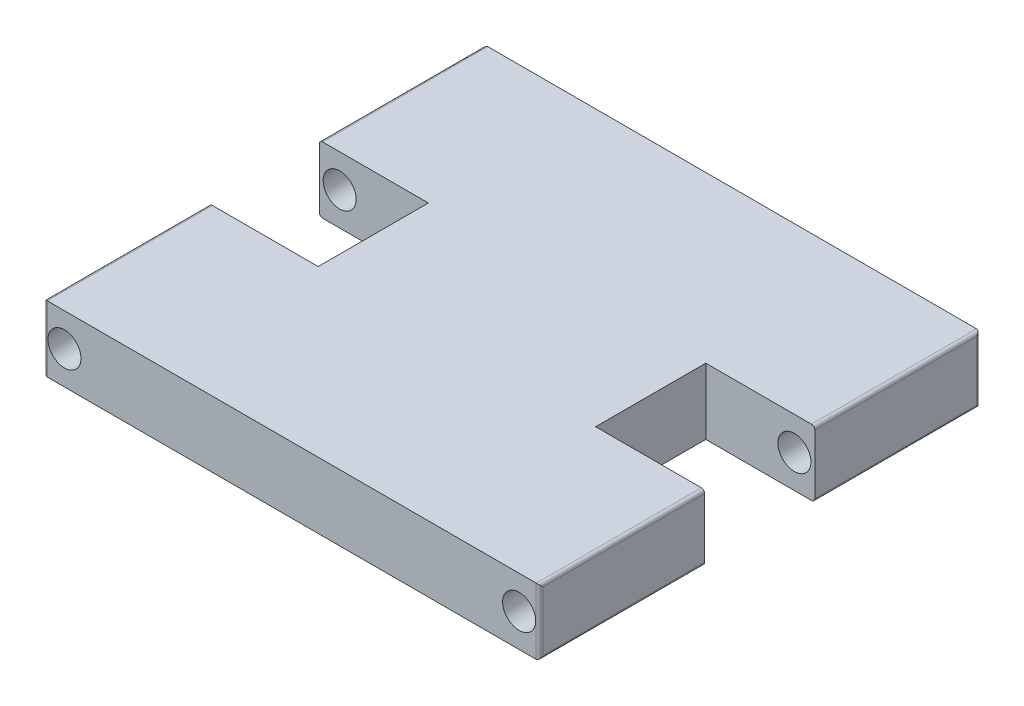
SolidWorks part; units mm, degrees
ref_plane "Piano frontale" through (0, 0, 0) normal (0, 0, 1) x (1, 0, 0)
ref_plane "Piano superiore" through (0, 0, 0) normal (0, 1, 0) x (1, 0, 0)
ref_plane "Piano destro" through (0, 0, 0) normal (1, 0, 0) x (0, 0, -1)
sketch "Schizzo1" plane through (0, 0, 0) normal (0, 1, 0) x (1, 0, 0)
  line L1 (3, 0) -> (447, 0)
  line L2 (0, 3) -> (0, 397)
  line L3 (3, 400) -> (447, 400)
  line L4 (450, 3) -> (450, 397)
  arc A0 (447, 400) -> (450, 397) centre (447, 397) cw
  arc A1 (447, 0) -> (450, 3) centre (447, 3) ccw
  arc A2 (3, 0) -> (0, 3) centre (3, 3) cw
  arc A3 (0, 397) -> (3, 400) centre (3, 397) cw
  point P7 (450, 400)
  point P12 (0, 0)
  point P15 (0, 400)
  dimension "D3" = 3
  dimension "D1" = 450
  dimension "D2" = 400
extrude "Estrusione-Estrusione1" add sketch "Schizzo1" along normal blind 60
sketch "Schizzo3" plane through (0, 0, 0) normal (0, 0, 1) x (1, 0, 0)
  line L0 (3, 60) -> (447, 60)
  line L1 (450, 57) -> (450, 3)
  line L2 (447, 0) -> (3, 0)
  line L3 (0, 3) -> (0, 57)
  line L4 (0, 30) -> (450, 30) construction
  line L5 (225, 60) -> (225, 0) construction
  arc A0 (447, 60) -> (450, 57) centre (447, 57) cw
  arc A1 (450, 3) -> (447, 0) centre (447, 3) cw
  arc A2 (3, 0) -> (0, 3) centre (3, 3) cw
  arc A3 (3, 60) -> (0, 57) centre (3, 57) ccw
  circle A4 centre (18.5, 30) radius 15
  circle A5 centre (431.5, 30) radius 15
  point P11 (450, 60)
  point P14 (450, 0)
  point P17 (0, 0)
  point P20 (0, 60)
  dimension "D1" = 3
  dimension "D2" = 30
  dimension "D3" = 30
  dimension "D4" = 413
  dimension "D5" = 206.5
extrude "Taglio-Estrusione2" cut sketch "Schizzo3" against normal through all both and the other way through all flip side to cut
sketch "Schizzo4" plane through (0, 0, 0) normal (0, 1, 0) x (1, 0, 0)
  line L0 (0, 200) -> (450, 200) construction
  line L1 (0, 397) -> (0, 3) construction
  line L2 (450, 397) -> (450, 3) construction
  line L4 (-1, 250) -> (99, 250)
  line L5 (-1, 250) -> (-1, 150)
  line L6 (-1, 150) -> (99, 150)
  line L7 (99, 250) -> (99, 150)
  line L8 (351, 250) -> (451, 250)
  line L9 (351, 250) -> (351, 150)
  line L10 (351, 150) -> (451, 150)
  line L11 (451, 250) -> (451, 150)
  dimension "D1" = 100
  dimension "D2" = 100
  dimension "D3" = 50
  dimension "D4" = 100
  dimension "D5" = 100
  dimension "D6" = 50
  dimension "D7" = 1
  dimension "D8" = 1
extrude "Taglio-Estrusione3" cut sketch "Schizzo4" along normal through all
